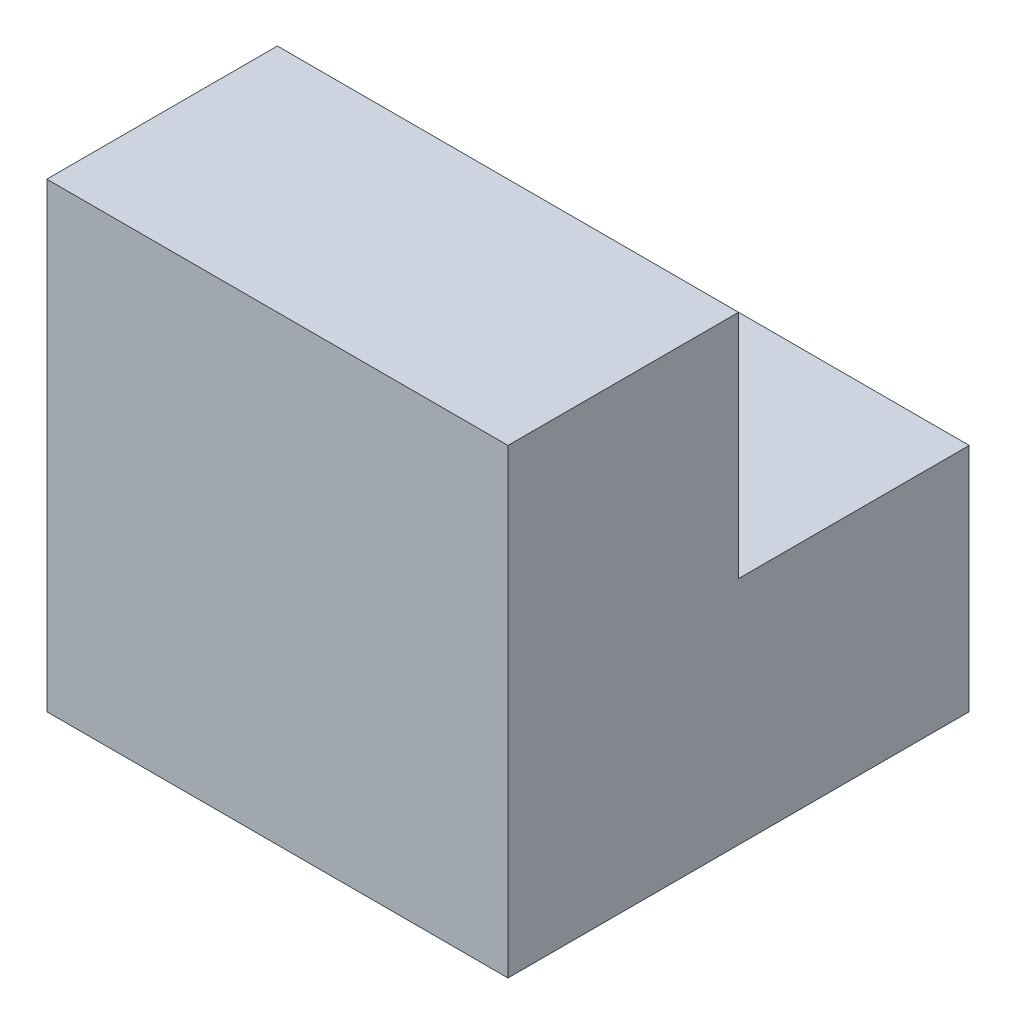
SolidWorks part; units mm, degrees
ref_plane "Front Plane" through (0, 0, 0) normal (0, 0, 1) x (1, 0, 0)
ref_plane "Top Plane" through (0, 0, 0) normal (0, 1, 0) x (1, 0, 0)
ref_plane "Right Plane" through (0, 0, 0) normal (1, 0, 0) x (0, 0, -1)
sketch "Sketch1" plane through (0, 0, 0) normal (0, 1, 0) x (1, 0, 0)
  line L1 (0, 0) -> (50.8, 0)
  line L2 (0, 0) -> (0, -50.8)
  line L3 (0, -50.8) -> (50.8, -50.8)
  line L4 (50.8, 0) -> (50.8, -50.8)
  dimension "D1" = 50.8
  dimension "D2" = 50.8
extrude "Boss-Extrude1" add sketch "Sketch1" along normal blind 25.4
sketch "Sketch2" plane through (0, 25.4, 0) normal (0, 1, 0) x (1, 0, 0)
  line L1 (25.4, -25.4) -> (50.8, -25.4)
  line L2 (25.4, -25.4) -> (25.4, -50.8)
  line L3 (25.4, -50.8) -> (50.8, -50.8)
  line L4 (50.8, -25.4) -> (50.8, -50.8)
  dimension "D1" = 25.4
  dimension "D2" = 25.4
extrude "Boss-Extrude2" add sketch "Sketch2" along normal blind 25.4
sketch "Sketch3" plane through (25.4, 0, 0) normal (-1, 0, 0) x (0, 0, 1)
  line L1 (25.4, 50.8) -> (50.8, 50.8)
  line L2 (25.4, 50.8) -> (25.4, 25.4)
  line L3 (25.4, 25.4) -> (50.8, 25.4)
  line L4 (50.8, 50.8) -> (50.8, 25.4)
extrude "Boss-Extrude3" add sketch "Sketch3" along normal blind 25.4
